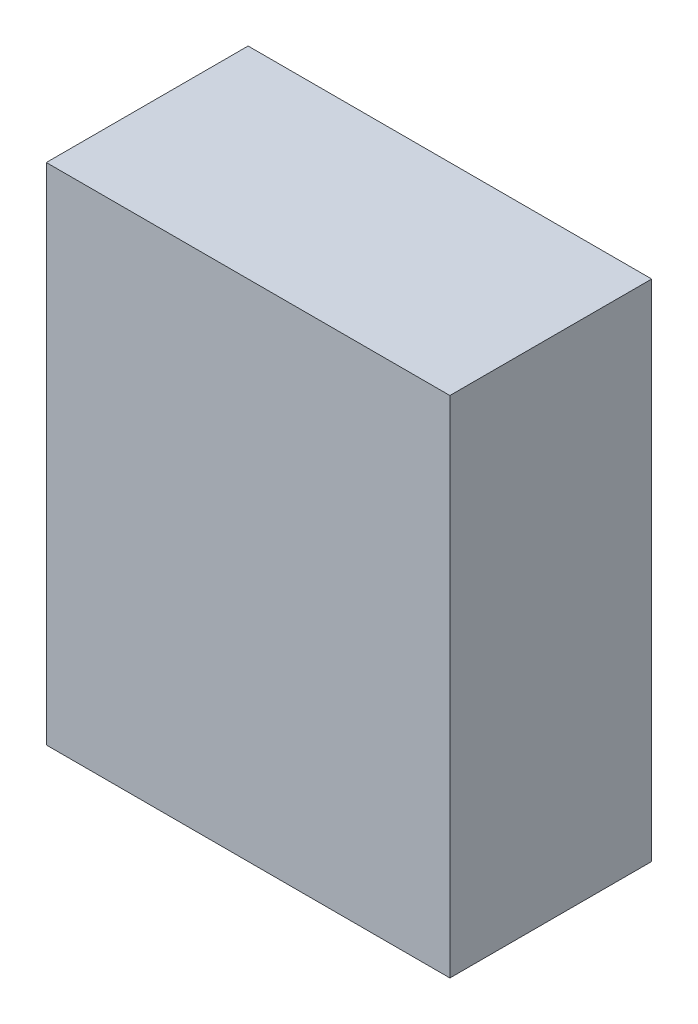
SolidWorks part; units mm, degrees
material "Copper"
ref_plane "Front Plane" through (0, 0, 0) normal (0, 0, 1) x (1, 0, 0)
ref_plane "Top Plane" through (0, 0, 0) normal (0, 1, 0) x (1, 0, 0)
ref_plane "Right Plane" through (0, 0, 0) normal (1, 0, 0) x (0, 0, -1)
sketch "BlockBase" plane through (0, 0, 0) normal (0, 0, 1) x (1, 0, 0)
  line L1 (-50.8, -63.5) -> (50.8, -63.5)
  line L2 (-50.8, -63.5) -> (-50.8, 63.5)
  line L3 (-50.8, 63.5) -> (50.8, 63.5)
  line L4 (50.8, -63.5) -> (50.8, 63.5)
  line L5 (-50.8, -63.5) -> (50.8, 63.5) construction
  line L6 (-50.8, 63.5) -> (50.8, -63.5) construction
  point P0 (0, 0)
  dimension "Length" = 101.6
  dimension "Width" = 127
extrude "Block" add sketch "BlockBase" along normal blind 50.8
